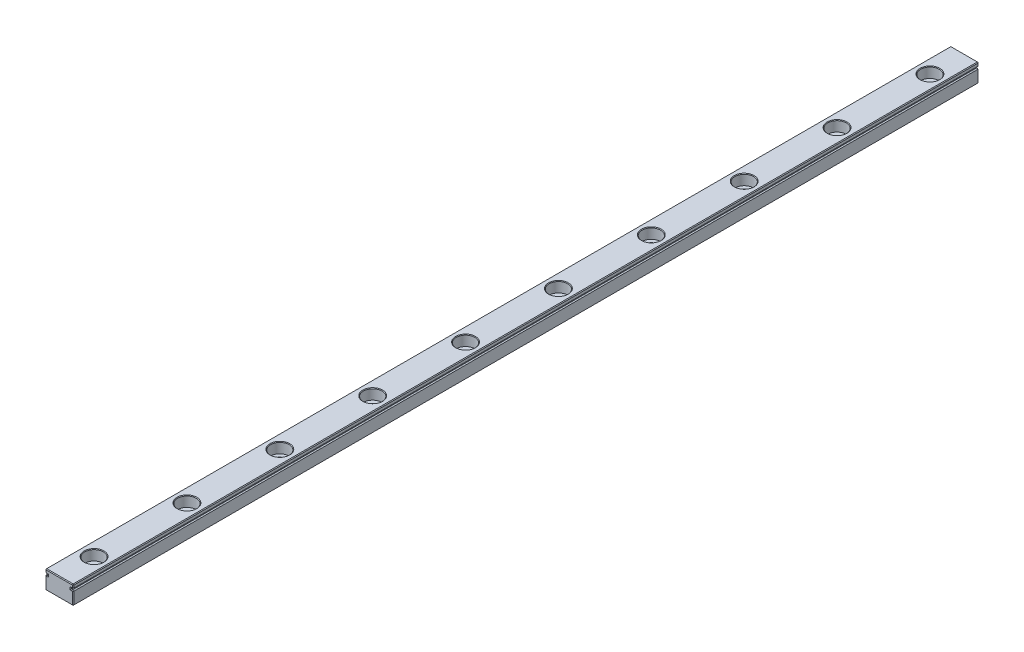
SolidWorks part; units mm, degrees
material "AISI 304"
ref_plane "Front Plane" through (0, 0, 0) normal (0, 0, 1) x (1, 0, 0)
ref_plane "Top Plane" through (0, 0, 0) normal (0, 1, 0) x (1, 0, 0)
ref_plane "Right Plane" through (0, 0, 0) normal (1, 0, 0) x (0, 0, -1)
sketch "Sketch1" plane through (0, 0, 0) normal (0, 0, 1) x (1, 0, 0)
  line L0 (0, 0) -> (0, 8) construction
  line L1 (0, 8) -> (12, 8)
  line L2 (0, 0) -> (12, 0)
  line L3 (0, 8) -> (0, 6.75)
  line L4 (0, 6.75) -> (0.5, 6.25) construction
  line L5 (0.5, 6.25) -> (1, 6.25)
  line L6 (0.5, 5.75) -> (0, 5.25) construction
  line L7 (0, 5.25) -> (0, 0)
  line L8 (1, 6.25) -> (1, 5.75)
  line L9 (1, 5.75) -> (0.5, 5.75)
  line L10 (0.5, 5.75) -> (0.75, 6) construction
  line L11 (0.75, 6) -> (0.5, 6.25) construction
  line L12 (0, 6.75) -> (0, 6.559)
  line L13 (0, 5.25) -> (0, 5.441)
  line L14 (6, 8) -> (6, 0) construction
  line L15 (11.25, 6) -> (11.5, 6.25) construction
  line L16 (11.5, 5.75) -> (11.25, 6) construction
  line L17 (11.5, 5.75) -> (12, 5.25) construction
  line L18 (12, 6.75) -> (11.5, 6.25) construction
  line L19 (12, 0) -> (12, 8) construction
  line L20 (12, 5.25) -> (12, 5.441)
  line L21 (12, 6.75) -> (12, 6.559)
  line L22 (11, 5.75) -> (11.5, 5.75)
  line L23 (11, 6.25) -> (11, 5.75)
  line L24 (12, 5.25) -> (12, 0)
  line L25 (11.5, 6.25) -> (11, 6.25)
  line L26 (12, 8) -> (12, 6.75)
  arc A0 (0, 5.441) -> (0.5, 5.75) centre (0, 6) ccw
  arc A1 (0.5, 6.25) -> (0, 6.559) centre (0, 6) ccw
  arc A2 (11.5, 6.25) -> (12, 6.559) centre (12, 6) cw
  arc A3 (12, 5.441) -> (11.5, 5.75) centre (12, 6) cw
  point P4 (1, 6)
  point P28 (11, 6)
  dimension "D1" = 8
  dimension "D2" = 6
  dimension "D3" = 0.5
  dimension "D4" = 45
  dimension "D5" = 2
  dimension "D6" = 1
extrude "Boss-Extrude1" add sketch "Sketch1" along normal blind 390
chamfer "Chamfer1" distance 0.3 angle 45 36 edges at (0, 0, 195) (12, 0, 195) (0, 8, 195) (12, 8, 195) (0.2939, 5.5245, 390) (0.75, 5.75, 390) (1, 6, 390) (0.75, 6.25, 390) (0.2939, 6.4755, 390) (0, 7.2795, 390) (6, 8, 390) (12, 7.2795, 390) (11.7061, 6.4755, 390) (11.25, 6.25, 390) (11, 6, 390) (11.25, 5.75, 390) (11.7061, 5.5245, 390) (12, 2.7205, 390) (6, 0, 390) (0, 2.7205, 390) (12, 2.7205, 0) (11.7061, 5.5245, 0) (11.25, 5.75, 0) (11, 6, 0) (11.25, 6.25, 0) (11.7061, 6.4755, 0) (12, 7.2795, 0) (6, 0, 0) (0, 2.7205, 0) (0.2939, 5.5245, 0) (0.75, 5.75, 0) (1, 6, 0) (0.75, 6.25, 0) (0.2939, 6.4755, 0) (0, 7.2795, 0) (6, 8, 0)
hole_wizard "CBORE for M5 Hex Head Bolt1" positions "3DSketch1" profile "Sketch3" counterbore size "M5" standard "ANSI Metric" end condition through all
sketch3d "3DSketch1"
  line L0 (6, 8, 0) -> (6, 8, 15) construction
  line L1 (11.7, 8, 0) -> (0.3, 8, 0) construction
  point P0 (6, 8, 15)
  dimension "D1" = 15
sketch "Sketch3" plane through (6, 8, 15) normal (1, 0, 0) x (0, 0, 1)
  line L0 (0, 0) -> (0, 8)
  line L1 (2.25, 7.75) -> (2.5, 8)
  line L2 (4, 4.5) -> (2.25, 4.5)
  line L3 (2.25, 4.5) -> (2.25, 7.75)
  line L5 (4, 4.5) -> (4, 0.25)
  line L6 (4, 0.25) -> (4.25, 0)
  line L7 (4.25, 0) -> (0, 0)
  line L8 (-4, 0.25) -> (-4.25, 0) construction
  line L11 (0, -6.35) -> (0, 107.95) construction
  line L12 (2.5, 8) -> (0, 8)
  line L13 (-2.25, 7.75) -> (-2.5, 8) construction
  dimension "Thru Hole Dia." = 4.5
  dimension "Thru Hole Depth" = 8
  dimension "C'Bore Dia." = 8
  dimension "C'Bore Depth" = 4.5
  dimension "Near C'Sink Dia." = 8.5
  dimension "Near C'Sink Angle" = 90
  dimension "Far C'Sink Dia." = 5
  dimension "Far C'Sink Angle" = 90
pattern_linear "LPattern1" count 10 spacing 40 along (0, 0, 1) of "CBORE for M5 Hex Head Bolt1"
